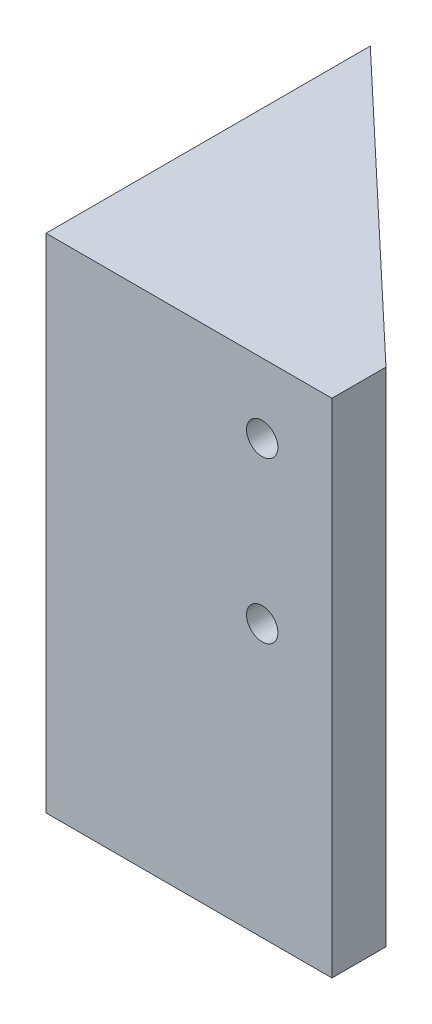
SolidWorks part; units mm, degrees
ref_plane "Front Plane" through (0, 0, 0) normal (0, 0, 1) x (1, 0, 0)
ref_plane "Top Plane" through (0, 0, 0) normal (0, 1, 0) x (1, 0, 0)
ref_plane "Right Plane" through (0, 0, 0) normal (1, 0, 0) x (0, 0, -1)
sketch "Sketch1" plane through (0, 0, 0) normal (0, 0, 1) x (1, 0, 0)
  line L1 (-10, -23.225) -> (10, -23.225)
  line L2 (-10, -23.225) -> (-10, 23.225)
  line L3 (-10, 23.225) -> (10, 23.225)
  line L4 (10, -23.225) -> (10, 23.225)
  line L5 (-10, -23.225) -> (10, 23.225) construction
  line L6 (-10, 23.225) -> (10, -23.225) construction
  point P0 (0, 0)
  dimension "D1" = 20
  dimension "D2" = 46.45
extrude "Boss-Extrude1" add sketch "Sketch1" along normal blind 5
sketch "Sketch2" plane through (0, 0, 5) normal (0, 0, 1) x (1, 0, 0)
  line L0 (10, -23.225) -> (10, 23.225) construction
  line L1 (10, 23.225) -> (-10, 23.225) construction
  circle A3 centre (3.55, 16.775) radius 1.45
  circle A4 centre (3.55, 1.935) radius 1.45
  point P8 (3.55, -3.9123)
  dimension "D1" = 2.9
  dimension "D6" = 2.9
  dimension "D2" = 6.45
  dimension "D3" = 6.45
  dimension "D4" = 14.84
  dimension "D5" = 6.45
sketch "Sketch4" plane through (0, 0, 0) normal (0, 1, 0) x (1, 0, 0)
  line L3 (3.55, -5) -> (-16.45, -5)
  line L5 (-16.45, -5) -> (-16.45, 25)
  line L6 (-16.45, 25) -> (10, 0)
  line L9 (2.1, -5) -> (5, -5) construction
  line L10 (3.55, -5) -> (10, -5)
  line L11 (10, -5) -> (10, 0)
  point P3 (3.55, -5)
  dimension "D1" = 20
  dimension "D2" = 30
extrude "Boss-Extrude4" add sketch "Sketch4" along normal up to surface and the other way up to surface up to face at (0, 23.225, 2.5) other way up to face at (0, -23.225, 2.5)
sketch "Sketch6" plane through (0, 0, 5) normal (0, 0, 1) x (1, 0, 0)
  circle A0 centre (3.55, 16.775) radius 1.45
  circle A1 centre (3.55, 1.935) radius 1.45
  point P6 (3.55, 1.775)
  point P7 (3.55, 16.775)
  dimension "D1" = 2.9
  dimension "D2" = 2.9
extrude "Cut-Extrude2" cut sketch "Sketch6" against normal blind 7.5
